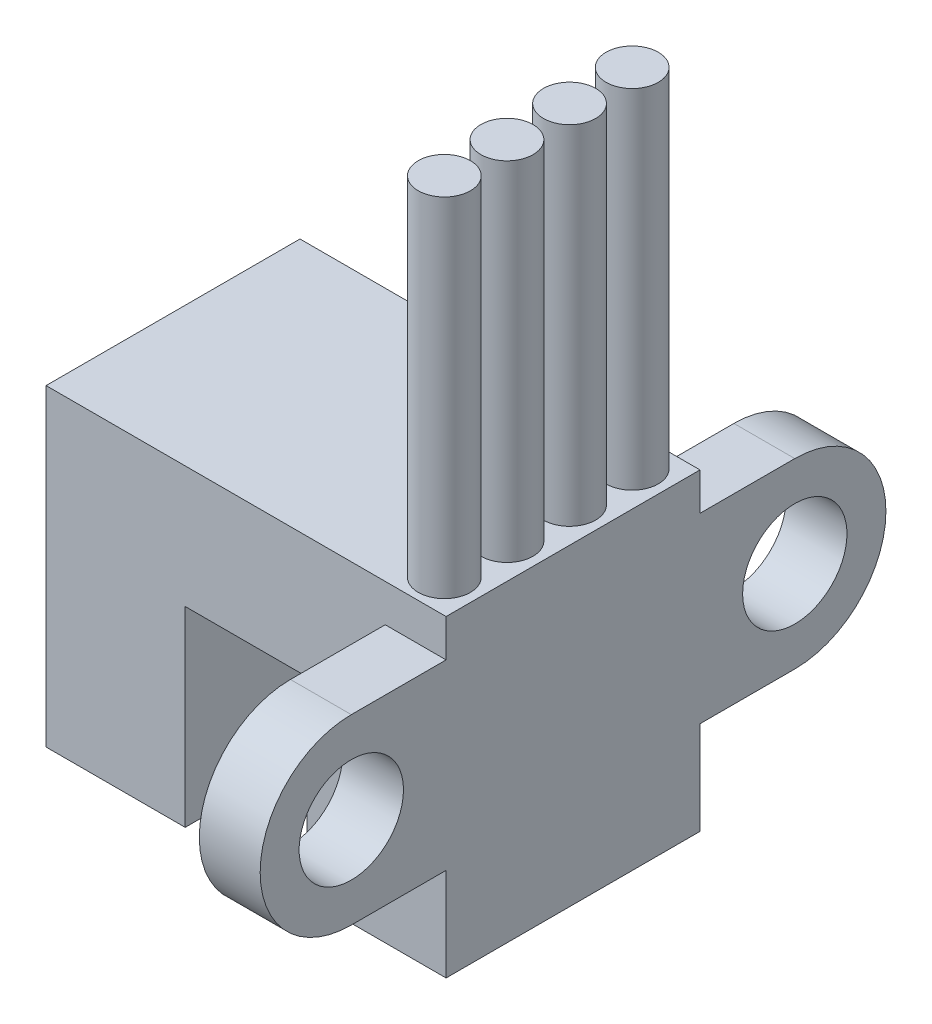
SolidWorks part; units mm, degrees
material "ABS"
ref_plane "Plan de face" through (0, 0, 0) normal (0, 0, 1) x (1, 0, 0)
ref_plane "Plan de dessus" through (0, 0, 0) normal (0, 1, 0) x (1, 0, 0)
ref_plane "Plan de droite" through (0, 0, 0) normal (1, 0, 0) x (0, 0, -1)
sketch "Esquisse1" plane through (0, 0, 0) normal (0, 0, 1) x (1, 0, 0)
  line L0 (1.75, 0) -> (-1.75, 0)
  line L1 (-1.75, 0) -> (-1.75, -5.5)
  line L2 (-1.75, -5.5) -> (-5.75, -5.5)
  line L3 (-5.75, -5.5) -> (-5.75, 3.5)
  line L4 (-5.75, 3.5) -> (5.75, 3.5)
  line L5 (0, 3.5) -> (0, 0) construction
  line L6 (1.75, -5.5) -> (5.75, -5.5)
  line L7 (1.75, 0) -> (1.75, -5.5)
  line L8 (5.75, -5.5) -> (5.75, 3.5)
  dimension "D1" = 5.75
  dimension "D2" = 1.75
  dimension "D3" = 9
  dimension "D4" = 5.5
extrude "Boss.-Extru.1" add sketch "Esquisse1" along normal mid plane 7.3
sketch "Esquisse2" plane through (5.75, 0, 0) normal (1, 0, 0) x (0, 0, -1)
  line L0 (0, 0) -> (0, 3.5) construction
  line L1 (-3.65, 3.5) -> (3.65, 3.5) construction
  line L2 (0, -0.2) -> (-6.375, -0.2) construction
  line L3 (-3.65, -5.5) -> (3.65, -5.5) construction
  line L4 (-6.375, 4) -> (-6.375, -4.8711) construction
  line L5 (-6.375, 2.42) -> (-3.65, 2.42)
  line L6 (-3.65, -5.5) -> (-3.65, 3.5) construction
  line L7 (-6.375, -2.82) -> (-3.65, -2.82)
  line L8 (-3.65, -2.82) -> (-3.65, 2.42)
  circle A0 centre (-6.375, -0.2) radius 1.5
  arc A1 (-6.375, 2.42) -> (-6.375, -2.82) centre (-6.375, -0.2) ccw
  dimension "D3" = 3
  dimension "D4" = 2.62
  dimension "D1" = 5.3
  dimension "D2" = 6.375
extrude "Boss.-Extru.2" add sketch "Esquisse2" against normal blind 1.75
mirror "Symétrie1" about plane through (0, 0, 0) normal (0, 0, 1) of "Boss.-Extru.2"
sketch "Esquisse3" plane through (0, 3.5, 0) normal (0, 1, 0) x (1, 0, 0)
  line L0 (4.75, 3.65) -> (4.75, -3.65) construction
  line L1 (5.75, 3.65) -> (-5.75, 3.65) construction
  line L2 (4, -3.65) -> (5.75, -3.65) construction
  line L3 (5.75, -3.65) -> (5.75, 3.65) construction
  line L4 (0, 0) -> (5.75, 0) construction
  circle A0 centre (4.75, 2.7) radius 0.75
  circle A1 centre (4.75, 0.9) radius 0.75
  circle A2 centre (4.75, -0.9) radius 0.75
  circle A3 centre (4.75, -2.7) radius 0.75
  dimension "D2" = 1.5
  dimension "D3" = 1.5
  dimension "D1" = 1
  dimension "D4" = 1.8
  dimension "D5" = 0.9
extrude "Boss.-Extru.3" add sketch "Esquisse3" along normal blind 10
